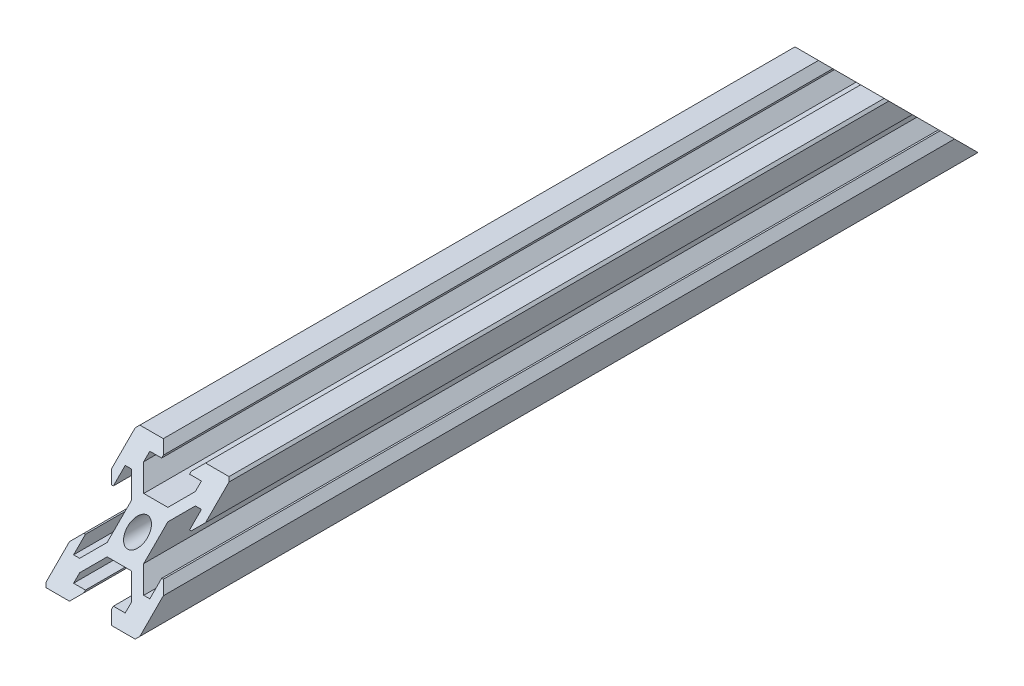
SolidWorks part; units mm, degrees
material "6061 Alloy"
ref_plane "Front Plane" through (0, 0, 0) normal (0, 0, 1) x (1, 0, 0)
ref_plane "Top Plane" through (0, 0, 0) normal (0, 1, 0) x (1, 0, 0)
ref_plane "Right Plane" through (0, 0, 0) normal (1, 0, 0) x (0, 0, -1)
sketch "Sketch1" plane through (0, 0, 0) normal (0, 0, 1) x (1, 0, 0)
  line L0 (15.6876, 55.3211) -> (115.0437, 55.3211) construction
  line L1 (5.5, 6.8294) -> (2.5706, 3.9)
  line L2 (0, 3.9) -> (0, 2.1)
  line L3 (10, 10) -> (1.4849, 1.4849)
  line L4 (10, 10) -> (4.5, 10)
  line L5 (1.4849, 1.4849) -> (3.9, 3.9) construction
  line L6 (10, -10) -> (-10, 10) construction
  line L7 (10, 10) -> (1.4849, 1.4849) construction
  line L8 (0, 0) -> (-10, -10) construction
  line L10 (0, 3.9) -> (2.5706, 3.9)
  line L12 (-3.9, -3.9) -> (0, 0) construction
  line L13 (-3.9, 3.9) -> (3.9, -3.9) construction
  line L14 (5.5, 6.8294) -> (5.5, 8.12)
  line L15 (5.5, 8.12) -> (2.62, 8.12)
  line L16 (2.62, 8.12) -> (4.5, 10)
  line L17 (0, 2.1) -> (0, 16.7618) construction
  arc A0 (1.4849, 1.4849) -> (0, 2.1) centre (0, 0) ccw
  point P2 (0, 0)
  point P7 (0, 0)
  dimension "D3" = 45
  dimension "D4" = 6.1
  dimension "D8" = 4.2
  dimension "D1" = 20
  dimension "D2" = 11
  dimension "D5" = 1.88
  dimension "D6" = 9
  dimension "D7" = 0.94
  dimension "D9" = 3.9
extrude "Boss-Extrude1" add sketch "Sketch1" along normal blind 179.6051
chamfer "Chamfer2" distance 0.5 angle 45 1 edges at (2.62, 8.12, 89.8026)
mirror "Mirror1" about plane through (10, 10, 179.6051) normal (-0.7071, 0.7071, 0) of bodies 102
chamfer "Chamfer1" distance 0.5 angle 45 1 edges at (10, 10, 89.8026)
mirror "Mirror4" about plane through (0, 3.9, 179.6051) normal (1, 0, 0) of bodies 103 104
mirror "Mirror5" about plane through (-3.9, 0, 179.6051) normal (0, 1, 0) of bodies 105
sketch "Sketch2" plane through (10, 0, 0) normal (1, 0, 0) x (0, 0, -1)
  line L0 (0, -10) -> (-20, 10)
  line L1 (-179.6051, 10) -> (0, 10) construction
  line L2 (-20, 10) -> (0, 10)
  line L3 (0, 10) -> (0, -10)
  line L4 (-89.8026, 9.5) -> (-89.8026, -9.5) construction
  line L5 (0, 9.5) -> (-179.6051, 9.5) construction
  line L6 (0, -9.5) -> (-179.6051, -9.5) construction
  line L7 (-159.6051, 10) -> (-179.6051, 10)
  line L8 (-179.6051, -10) -> (-159.6051, 10)
  line L9 (-179.6051, 10) -> (-179.6051, -10)
  dimension "D1" = 45
extrude "Cut-Extrude1" cut sketch "Sketch2" against normal up to surface (20 mm away) up to face at (-10, 7, 89.8026)
